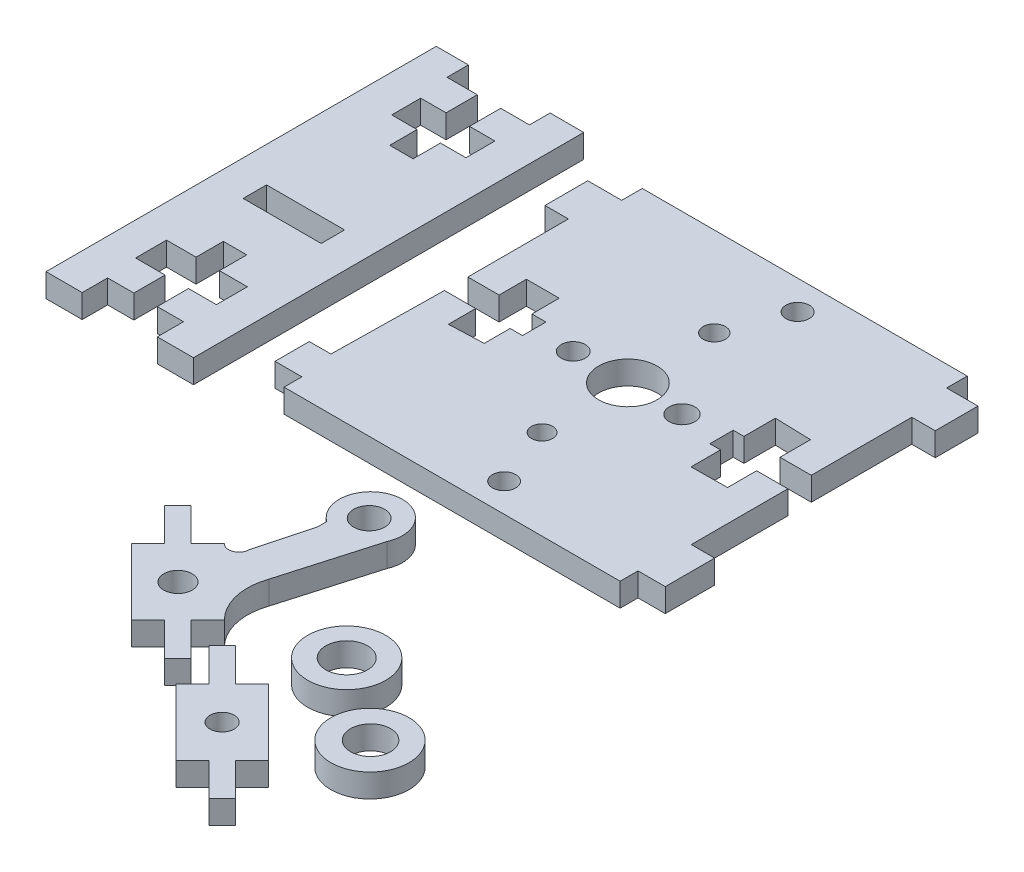
SolidWorks part; units mm, degrees
ref_plane "Front Plane" through (0, 0, 0) normal (0, 0, 1) x (1, 0, 0)
ref_plane "Top Plane" through (0, 0, 0) normal (0, 1, 0) x (1, 0, 0)
ref_plane "Right Plane" through (0, 0, 0) normal (1, 0, 0) x (0, 0, -1)
sketch "Sketch6" plane through (0, 0, -6.8736) normal (0, 1, 0) x (1, 0, 0)
  line L2 (242.3822, 6.8367) -> (239.3822, 6.8367)
  line L3 (239.3822, 6.8367) -> (239.3822, -6.0426)
  line L4 (239.3822, -6.0426) -> (235.3822, -6.0426)
  line L5 (235.3822, -6.0426) -> (235.3822, -2.1453)
  line L6 (235.3822, -2.1453) -> (230.7498, -2.0047)
  line L7 (230.7498, -2.0047) -> (230.7498, -6.0426)
  line L8 (230.7498, -6.0426) -> (229.3822, -6.0426)
  line L9 (229.3822, -6.0426) -> (229.3822, -9.0426)
  line L10 (229.3822, -9.0426) -> (230.7487, -9.0426)
  line L11 (230.7487, -9.0426) -> (230.7487, -12.8135)
  line L12 (230.7487, -12.8135) -> (235.3822, -12.7673)
  line L13 (235.3822, -12.7673) -> (235.3822, -9.0426)
  line L14 (235.3822, -9.0426) -> (239.3822, -9.0426)
  line L15 (239.3822, -9.0426) -> (239.3822, -21.4213)
  line L16 (239.3822, -21.4213) -> (242.3822, -21.4213)
  line L20 (192.3822, -23.3617) -> (195.1572, -23.3617)
  line L21 (195.3822, -9.0426) -> (199.3822, -9.0426)
  line L22 (199.3822, -9.0426) -> (199.3822, -12.5391)
  line L23 (199.3822, -12.5391) -> (203.7977, -12.3609)
  line L24 (203.7977, -12.3609) -> (203.7977, -9.0426)
  line L25 (203.7977, -9.0426) -> (205.3822, -9.0426)
  line L26 (205.3822, -9.0426) -> (205.3822, -6.0426)
  line L27 (205.3822, -6.0426) -> (203.5871, -6.0426)
  line L28 (203.5871, -6.0426) -> (203.5871, -2.5434)
  line L29 (203.5871, -2.5434) -> (199.3822, -2.5434)
  line L30 (199.3822, -2.5434) -> (199.3822, -6.0426)
  line L31 (199.3822, -6.0426) -> (195.3822, -6.0426)
  line L32 (195.3822, -6.0426) -> (195.3822, 6.8366)
  line L33 (195.3822, 6.8366) -> (192.3822, 6.8366)
  line L35 (195.1572, -23.3617) -> (195.3822, -9.0426)
  line L36 (171.8834, 17.524) -> (171.8834, 14.7799)
  line L37 (171.8834, 14.7799) -> (175.7635, 14.7799)
  line L38 (175.7635, 14.7799) -> (175.7635, 10.7799)
  line L39 (175.7635, 10.7799) -> (172.5162, 10.7799)
  line L40 (172.5162, 10.7799) -> (172.5162, 7.063)
  line L41 (172.5162, 7.063) -> (175.7635, 7.063)
  line L42 (175.7635, 7.063) -> (175.7635, 3.563)
  line L43 (175.7635, 3.563) -> (178.7635, 3.563)
  line L44 (178.7635, 3.563) -> (178.7635, 7.063)
  line L45 (178.7635, 7.063) -> (182.0281, 7.063)
  line L46 (182.0281, 7.063) -> (182.0281, 10.7799)
  line L47 (182.0281, 10.7799) -> (178.7635, 10.7799)
  line L48 (178.7635, 10.7799) -> (178.7635, 14.7799)
  line L49 (178.7635, 14.7799) -> (182.4525, 14.7799)
  line L50 (182.4525, 14.7799) -> (182.4525, 17.4216)
  line L51 (182.4525, 17.4216) -> (186.7635, 17.4216)
  line L52 (186.7635, 17.4216) -> (186.7635, -32.5784)
  line L53 (186.7635, -32.5784) -> (182.1277, -32.5784)
  line L54 (182.1277, -32.5784) -> (182.1277, -29.2201)
  line L55 (182.1277, -29.2201) -> (178.7635, -29.2201)
  line L56 (178.7635, -29.2201) -> (178.7635, -25.2201)
  line L57 (178.7635, -25.2201) -> (182.3404, -25.2201)
  line L58 (182.3404, -25.2201) -> (182.3404, -21.2526)
  line L59 (182.3404, -21.2526) -> (178.7635, -21.2526)
  line L60 (178.7635, -21.2526) -> (178.7635, -17.7526)
  line L61 (178.7635, -17.7526) -> (175.7635, -17.7526)
  line L62 (175.7635, -17.7526) -> (175.7635, -21.2526)
  line L63 (175.7635, -21.2526) -> (171.9828, -21.2526)
  line L64 (171.9828, -21.2526) -> (171.9828, -25.2201)
  line L65 (171.9828, -25.2201) -> (175.7635, -25.2201)
  line L66 (175.7635, -25.2201) -> (175.7635, -29.2201)
  line L67 (175.7635, -29.2201) -> (172.4042, -29.2201)
  line L68 (172.4042, -29.2201) -> (172.4042, -32.476)
  line L69 (172.4042, -32.476) -> (167.7635, -32.476)
  line L70 (167.7635, -32.476) -> (167.7635, 17.524)
  line L71 (167.7635, 17.524) -> (171.8834, 17.524)
  line L72 (172.2635, -8.7201) -> (182.2635, -8.7201)
  line L73 (182.2635, -8.7201) -> (182.2635, -11.7201)
  line L74 (182.2635, -11.7201) -> (172.2635, -11.7201)
  line L75 (172.2635, -11.7201) -> (172.2635, -8.7201)
  line L84 (217.8601, -59.7241) -> (215.7388, -61.8454)
  line L85 (215.7388, -61.8454) -> (219.9814, -66.0881)
  line L86 (219.9814, -66.0881) -> (218.2844, -67.7851)
  line L87 (218.2844, -67.7851) -> (214.0417, -63.5425)
  line L88 (214.0417, -63.5425) -> (211.9204, -65.6638)
  line L89 (211.9204, -65.6638) -> (203.4351, -57.1785)
  line L90 (203.4351, -57.1785) -> (205.5564, -55.0572)
  line L91 (205.5564, -55.0572) -> (201.3138, -50.8146)
  line L92 (201.3138, -50.8146) -> (203.0109, -49.1175)
  line L93 (203.0109, -49.1175) -> (207.2535, -53.3602)
  line L94 (207.2535, -53.3602) -> (209.3748, -51.2388)
  line L95 (211.633, -50.3035) -> (213.4745, -43.4567)
  line L96 (216.1631, -52.2995) -> (219.5483, -40.5807)
  line L97 (213.4745, -43.4567) -> (213.4745, -42.2199)
  line L98 (227.7596, -63.9668) -> (236.245, -72.452)
  line L99 (236.245, -72.452) -> (234.1237, -74.5733)
  line L100 (234.1237, -74.5733) -> (238.3663, -78.816)
  line L101 (238.3663, -78.816) -> (236.6692, -80.513)
  line L102 (236.6692, -80.513) -> (232.4266, -76.2704)
  line L103 (232.4266, -76.2704) -> (230.3053, -78.3917)
  line L104 (230.3053, -78.3917) -> (221.8199, -69.9065)
  line L105 (221.8199, -69.9065) -> (223.9412, -67.7851)
  line L106 (223.9412, -67.7851) -> (219.6986, -63.5425)
  line L107 (219.6986, -63.5425) -> (221.3956, -61.8454)
  line L108 (221.3956, -61.8454) -> (225.6383, -66.0881)
  line L109 (225.6383, -66.0881) -> (227.7596, -63.9668)
  line L118 (242.3822, -27.7516) -> (238.8902, -27.7516)
  line L119 (238.8902, -27.7516) -> (238.8902, -30.0426)
  line L120 (192.3822, -27.7516) -> (195.8238, -27.7516)
  line L121 (195.8238, -27.7516) -> (195.8238, -30.0426)
  line L122 (242.3822, -27.7516) -> (242.3822, -21.4213)
  line L123 (238.8902, -30.0426) -> (195.8238, -30.0426)
  line L124 (192.3822, -27.7516) -> (192.3822, -23.3617)
  line L125 (238.3663, 14.9574) -> (238.3663, 12.3177)
  line L126 (238.3663, 12.3177) -> (242.3822, 12.3177)
  line L127 (192.3822, 12.3177) -> (196.7311, 12.3177)
  line L128 (196.7311, 12.3177) -> (196.7311, 14.9574)
  line L129 (196.7311, 14.9574) -> (238.3663, 14.9574)
  line L130 (192.3822, 12.3177) -> (192.3822, 6.8366)
  line L131 (242.3822, 6.8367) -> (242.3822, 12.3177)
  circle A0 centre (217.3822, -7.5426) radius 3.75
  circle A1 centre (210.3822, -7.5426) radius 1.5333
  circle A2 centre (217.3726, 3.5398) radius 1.4239
  circle A3 centre (224.3329, -7.5545) radius 1.6482
  circle A4 centre (220.3822, 11.2074) radius 1.5
  circle A5 centre (217.3822, -18.5367) radius 1.3524
  circle A6 centre (220.3686, -26.382) radius 1.4891
  arc A13 (209.3748, -51.2388) -> (211.633, -50.3035) centre (210.3102, -50.3035) ccw
  arc A14 (217.8601, -59.7241) -> (216.1631, -52.2995) centre (222.9237, -54.6605) cw
  circle A15 centre (215.824, -39.1328) radius 1.9876
  arc A16 (219.5483, -40.5807) -> (213.4745, -42.2199) centre (215.8488, -38.9451) ccw
  circle A17 centre (210.6476, -58.4513) radius 1.8201
  circle A18 centre (229.8748, -56.0569) radius 2.6763
  circle A19 centre (229.8748, -56.0569) radius 5
  circle A20 centre (240.5423, -63.668) radius 2.5644
  circle A21 centre (240.5012, -63.7091) radius 5.004
  circle A22 centre (229.0324, -71.1792) radius 1.55
extrude "Boss-Extrude1" add sketch "Sketch6" along normal blind 3
